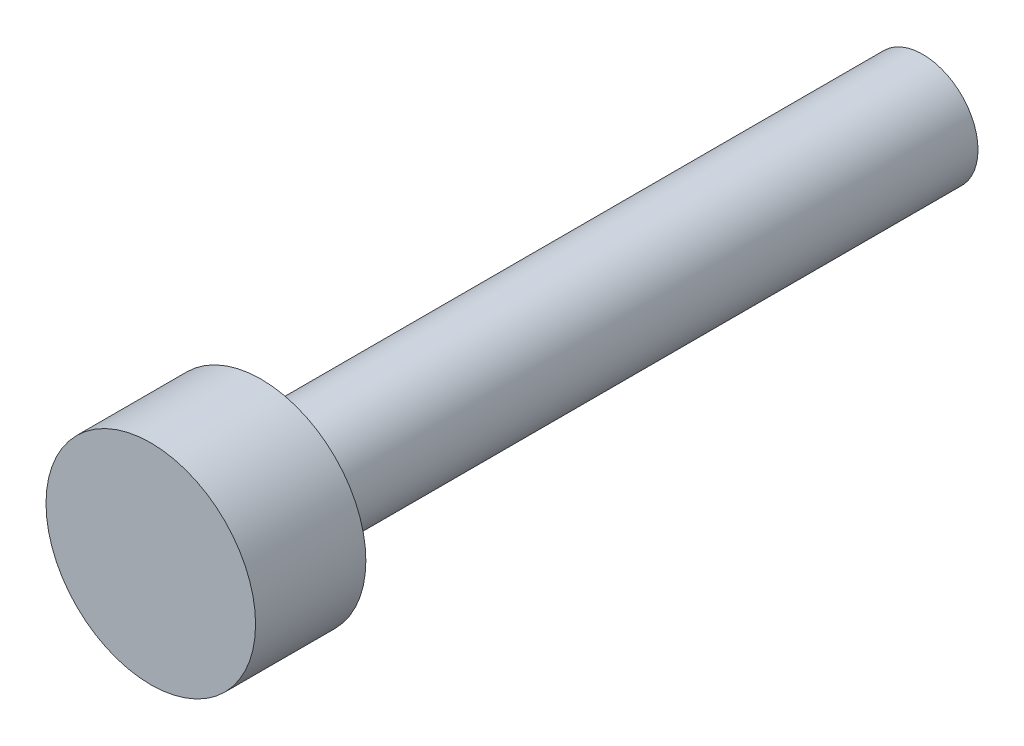
SolidWorks part; units mm, degrees
ref_plane "Front Plane" through (0, 0, 0) normal (0, 0, 1) x (1, 0, 0)
ref_plane "Top Plane" through (0, 0, 0) normal (0, 1, 0) x (1, 0, 0)
ref_plane "Right Plane" through (0, 0, 0) normal (1, 0, 0) x (0, 0, -1)
sketch "Sketch1" plane through (0, 0, 0) normal (0, 0, 1) x (1, 0, 0)
  circle A0 centre (0, 0) radius 1
extrude "Thread_Envelope" add sketch "Sketch1" along normal blind 12 from offset 12
sketch "Sketch2" plane through (0, 0, 0) normal (0, 0, 1) x (1, 0, 0)
  circle A0 centre (0, 0) radius 1.9
extrude "Head_Envelope" add sketch "Sketch2" along normal blind 2
